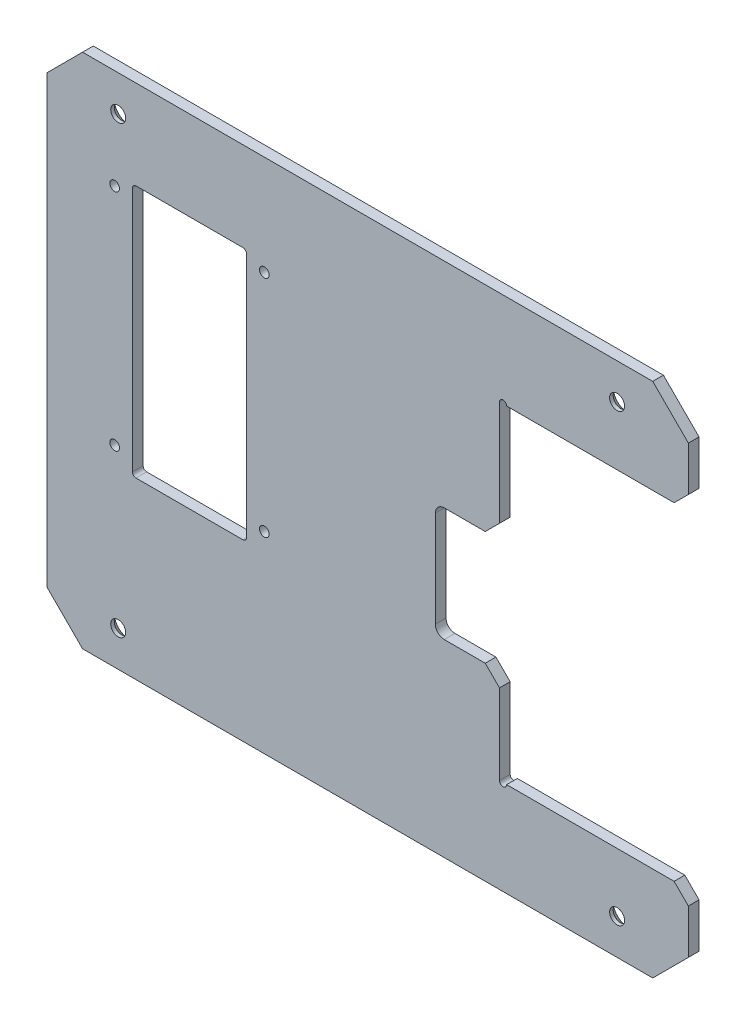
SolidWorks part; units mm, degrees
ref_plane "前视基准面" through (0, 0, 0) normal (0, 0, 1) x (1, 0, 0)
ref_plane "上视基准面" through (0, 0, 0) normal (0, 1, 0) x (1, 0, 0)
ref_plane "右视基准面" through (0, 0, 0) normal (1, 0, 0) x (0, 0, -1)
sketch "草图1" plane through (0, 0, 0) normal (0, 0, 1) x (1, 0, 0)
  line L1 (90, -72.5) -> (-90, -72.5)
  line L2 (90, -72.5) -> (90, 72.5)
  line L3 (90, 72.5) -> (-90, 72.5)
  line L4 (-90, -72.5) -> (-90, 72.5)
  line L5 (90, -72.5) -> (-90, 72.5) construction
  line L6 (90, 72.5) -> (-90, -72.5) construction
  point P0 (0, 0)
  dimension "D1" = 145
  dimension "D2" = 180
extrude "凸台-拉伸1" add sketch "草图1" along normal mid plane 3
sketch "草图2" plane through (0, 0, 1.5) normal (0, 0, 1) x (1, 0, 0)
  line L0 (90, 46) -> (37, 46)
  line L1 (90, -72.5) -> (90, 72.5) construction
  line L2 (37, 46) -> (37, -46)
  line L3 (37, -46) -> (90, -46)
  line L4 (90, -46) -> (90, 46)
  line L5 (90, 72.5) -> (-90, 72.5) construction
  line L6 (-90, 72.5) -> (-90, -72.5) construction
  line L7 (70, -62.5) -> (-70, -62.5) construction
  line L8 (70, -62.5) -> (70, 62.5) construction
  line L9 (70, 62.5) -> (-70, 62.5) construction
  line L10 (-70, -62.5) -> (-70, 62.5) construction
  line L11 (70, -62.5) -> (-70, 62.5) construction
  line L12 (70, 62.5) -> (-70, -62.5) construction
  circle A0 centre (-70, 62.5) radius 2.1
  circle A1 centre (-70, -62.5) radius 2.1
  circle A2 centre (70, -62.5) radius 2.1
  circle A3 centre (70, 62.5) radius 2.1
  point P5 (37, 0)
  point P10 (0, 0)
  dimension "D3" = 4.2
  dimension "D1" = 26.5
  dimension "D2" = 53
  dimension "D4" = 10
  dimension "D5" = 20
extrude "切除-拉伸1" cut sketch "草图2" against normal through all
sketch "草图4" plane through (0, 0, 1.5) normal (0, 0, 1) x (1, 0, 0)
  line L0 (37, 46) -> (37, -46) construction
  line L1 (19, -19.5) -> (37, -19.5)
  line L2 (19, -19.5) -> (19, 12.5)
  line L3 (19, 12.5) -> (37, 12.5)
  line L4 (37, -19.5) -> (37, 12.5)
  line L5 (19, -19.5) -> (37, 12.5) construction
  line L6 (19, 12.5) -> (37, -19.5) construction
  line L7 (90, 72.5) -> (-90, 72.5) construction
  line L8 (-90, -72.5) -> (90, -72.5) construction
  point P0 (28, -3.5)
  dimension "D1" = 60
  dimension "D2" = 53
  dimension "D3" = 18
extrude "切除-拉伸3" cut sketch "草图4" against normal through all
sketch "草图3" plane through (0, 0, 1.5) normal (0, 0, 1) x (1, 0, 0)
  line L0 (90, 46) -> (37, 46) construction
  line L1 (37, -46) -> (90, -46) construction
  circle A0 centre (38, 46) radius 1
  circle A1 centre (38, -46) radius 1
  dimension "D1" = 2
extrude "切除-拉伸2" cut sketch "草图3" against normal through all
fillet "圆角1" radius 2.5 2 edges at (19, -19.5, 0) (19, 12.5, 0)
chamfer "倒角1" distance 2 angle 45 4 edges at (72.1, -62.5, -1.5) (-67.9, -62.5, -1.5) (-67.9, 62.5, -1.5) (72.1, 62.5, -1.5)
chamfer "倒角2" distance 10 angle 45 4 edges at (-90, 72.5, 0) (90, 72.5, 0) (90, -72.5, 0) (-90, -72.5, 0)
chamfer "倒角3" distance 4 angle 45 4 edges at (90, -46, 0) (90, 46, 0) (37, -19.5, 0) (37, 12.5, 0)
sketch "草图5" plane through (0, 0, 1.5) normal (0, 0, 1) x (1, 0, 0)
  line L1 (-29, -18.5) -> (-71, -18.5) construction
  line L2 (-29, -18.5) -> (-29, 44.5) construction
  line L3 (-29, 44.5) -> (-71, 44.5) construction
  line L4 (-71, -18.5) -> (-71, 44.5) construction
  line L5 (-29, -18.5) -> (-71, 44.5) construction
  line L6 (-29, 44.5) -> (-71, -18.5) construction
  line L7 (-26, -21.5) -> (-74, -21.5) construction
  line L8 (-26, -21.5) -> (-26, 47.5) construction
  line L9 (-26, 47.5) -> (-74, 47.5) construction
  line L10 (-74, -21.5) -> (-74, 47.5) construction
  line L11 (-26, -21.5) -> (-74, 47.5) construction
  line L12 (-26, 47.5) -> (-74, -21.5) construction
  line L13 (80, 72.5) -> (-80, 72.5) construction
  line L14 (19, 10) -> (19, -17) construction
  line L15 (-34, -23.5) -> (-66, -23.5)
  line L16 (-34, -23.5) -> (-34, 47.5)
  line L17 (-34, 47.5) -> (-66, 47.5)
  line L18 (-66, -23.5) -> (-66, 47.5)
  line L19 (-34, -23.5) -> (-66, 47.5) construction
  line L20 (-34, 47.5) -> (-66, -23.5) construction
  circle A0 centre (-71, 44.5) radius 1.35
  circle A1 centre (-29, 44.5) radius 1.35
  circle A2 centre (-71, -18.5) radius 1.35
  circle A3 centre (-29, -18.5) radius 1.35
  point P7 (-50, 12)
  point P18 (-50, 13)
  point P21 (-50, 13)
  dimension "D5" = 2.7
  dimension "D1" = 42
  dimension "D2" = 63
  dimension "D3" = 48
  dimension "D4" = 69
  dimension "D6" = 25
  dimension "D7" = 5
  dimension "D8" = 71
  dimension "D9" = 45
extrude "切除-拉伸4" cut sketch "草图5" against normal through all
fillet "圆角2" radius 1 4 edges at (-34, -23.5, 0) (-66, -23.5, 0) (-34, 47.5, 0) (-66, 47.5, 0)
